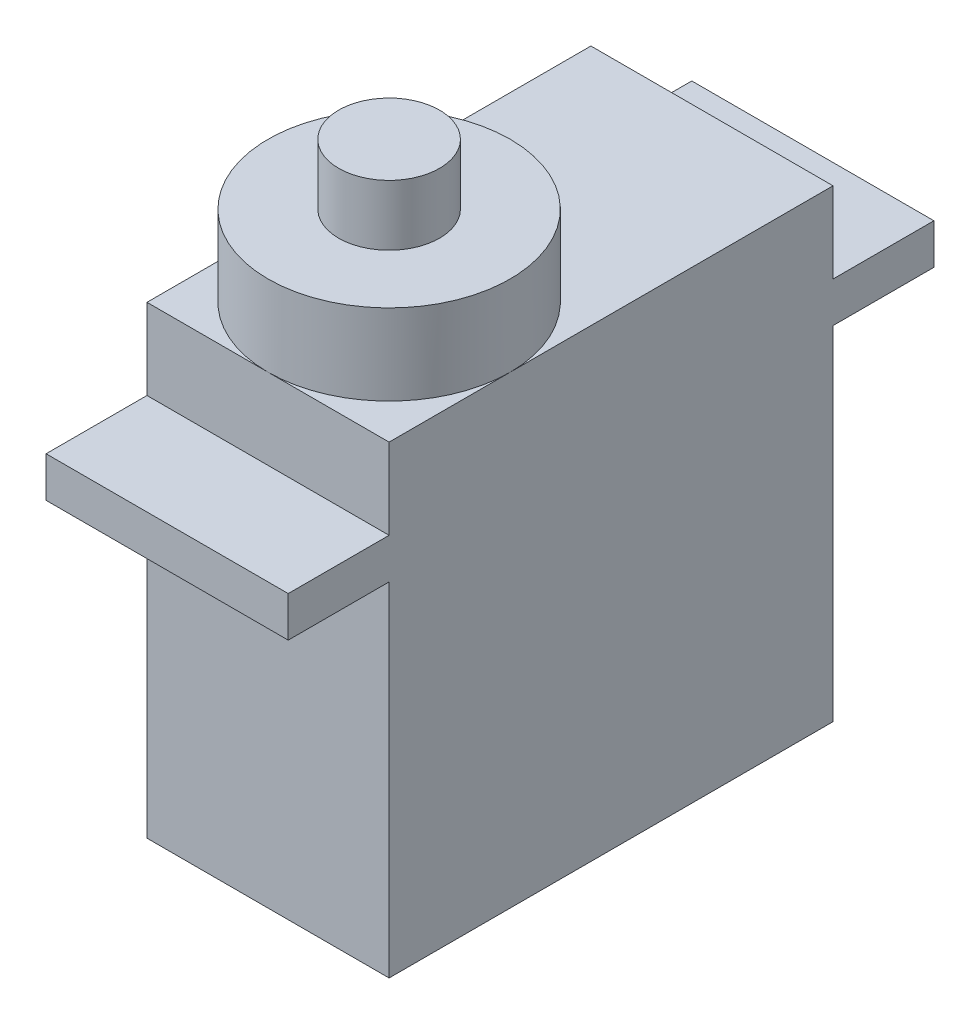
SolidWorks part; units mm, degrees
ref_plane "Front Plane" through (0, 0, 0) normal (0, 0, 1) x (1, 0, 0)
ref_plane "Top Plane" through (0, 0, 0) normal (0, 1, 0) x (1, 0, 0)
ref_plane "Right Plane" through (0, 0, 0) normal (1, 0, 0) x (0, 0, -1)
sketch "Sketch1" plane through (0, 0, 0) normal (0, 1, 0) x (1, 0, 0)
  line L1 (6, -11) -> (-6, -11)
  line L2 (6, -11) -> (6, 11)
  line L3 (6, 11) -> (-6, 11)
  line L4 (-6, -11) -> (-6, 11)
  line L5 (6, -11) -> (-6, 11) construction
  line L6 (6, 11) -> (-6, -11) construction
  point P0 (0, 0)
  dimension "D1" = 22
  dimension "D2" = 12
extrude "Boss-Extrude1" add sketch "Sketch1" along normal blind 23
sketch "Sketch2" plane through (0, 23, 0) normal (0, 1, 0) x (1, 0, 0)
  line L1 (-6, 11) -> (-6, -11) construction
  line L2 (6, -11) -> (6, 11) construction
  line L3 (-6, -11) -> (6, -11) construction
  circle A1 centre (0, -5) radius 6
sketch "Sketch3" plane through (0, 0, -11) normal (0, 0, -1) x (-1, 0, 0)
  line L0 (-6, 23) -> (-6, 0) construction
  line L1 (-6, 19) -> (6, 19)
  line L2 (-6, 19) -> (-6, 17)
  line L3 (-6, 17) -> (6, 17)
  line L4 (6, 19) -> (6, 17)
  line L5 (6, 23) -> (6, 0) construction
  line L6 (-6, 23) -> (6, 23) construction
  dimension "D1" = 4
  dimension "D2" = 2
extrude "Boss-Extrude3" add sketch "Sketch3" along normal blind 5 contours L3 L4 L1 L2
ref_plane "Plane1" through (0, 0, 0) normal (0, 0, 1) x (1, 0, 0)
mirror "Mirror1" about plane through (0, 0, 0) normal (0, 0, 1) of "Boss-Extrude3"
extrude "Boss-Extrude4" add sketch "Sketch2" along normal blind 4 contours A1
sketch "Sketch4" plane through (0, 27, 0) normal (0, 1, 0) x (1, 0, 0)
  circle A0 centre (0, -5) radius 2.5
  dimension "D1" = 5
extrude "Boss-Extrude5" add sketch "Sketch4" along normal blind 3
